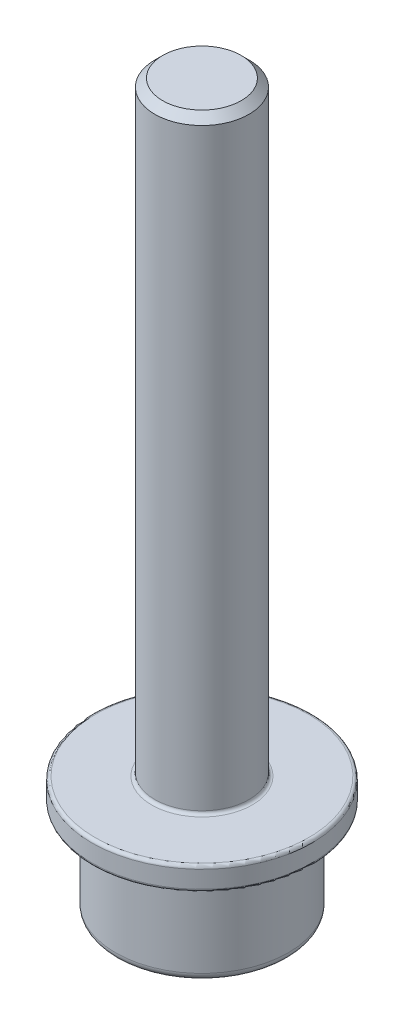
SolidWorks part; units mm, degrees
ref_plane "Front Plane" through (0, 0, 0) normal (0, 0, 1) x (1, 0, 0)
ref_plane "Top Plane" through (0, 0, 0) normal (0, 1, 0) x (1, 0, 0)
ref_plane "Right Plane" through (0, 0, 0) normal (1, 0, 0) x (0, 0, -1)
sketch "Sketch1" plane through (0, 0, 0) normal (0, 1, 0) x (1, 0, 0)
  circle A0 centre (0, 0) radius 2.75
  dimension "D1" = 5.5
extrude "Boss-Extrude1" add sketch "Sketch1" along normal blind 3
sketch "Sketch2" plane through (0, 3, 0) normal (0, 1, 0) x (1, 0, 0)
  circle A0 centre (0, 0) radius 1.5
  dimension "D1" = 3
extrude "Boss-Extrude2" add sketch "Sketch2" along normal blind 20 contours A0
sketch "Sketch3" plane through (0, 0, 0) normal (0, -1, 0) x (1, 0, 0)
  line L1 (0.9342, 0.9746) -> (-0.3769, 1.2963)
  line L2 (-0.3769, 1.2963) -> (-1.3111, 0.3217)
  line L3 (-1.3111, 0.3217) -> (-0.9342, -0.9746)
  line L4 (-0.9342, -0.9746) -> (0.3769, -1.2963)
  line L5 (0.3769, -1.2963) -> (1.3111, -0.3217)
  line L6 (1.3111, -0.3217) -> (0.9342, 0.9746)
  circle A0 centre (0, 0) radius 1.1691 construction
  dimension "D1" = 2.7
extrude "Cut-Extrude1" cut sketch "Sketch3" against normal blind 1.5
chamfer "Chamfer1" distance 0.25 distance2 0.25 6 edges at (-0.2786, 0, -1.1355) (-1.1226, 0, -0.3264) (-0.844, 0, 0.809) (0.2786, 0, 1.1355) (1.1226, 0, 0.3264) (0.844, 0, -0.809)
fillet "Fillet1" radius 0.25 1 edges at (0, 0, 2.75)
chamfer "Chamfer2" distance 0.25 angle 45 1 edges at (0, 23, 1.5)
fillet "Fillet2" radius 0.1 1 edges at (0, 3, 2.75)
sketch "Sketch4" plane through (0, 3, 0) normal (0, 1, 0) x (1, 0, 0)
  circle A0 centre (0, 0) radius 1.5
  circle A1 centre (0, 0) radius 3.5
  circle A2 centre (0, 0) radius 1.5 construction
  dimension "D1" = 7
extrude "Boss-Extrude3" add sketch "Sketch4" along normal blind 0.75
fillet "Fillet3" radius 0.1 3 edges at (0, 3.75, 1.5) (0, 3.75, 3.5) (0, 3, 3.5)
